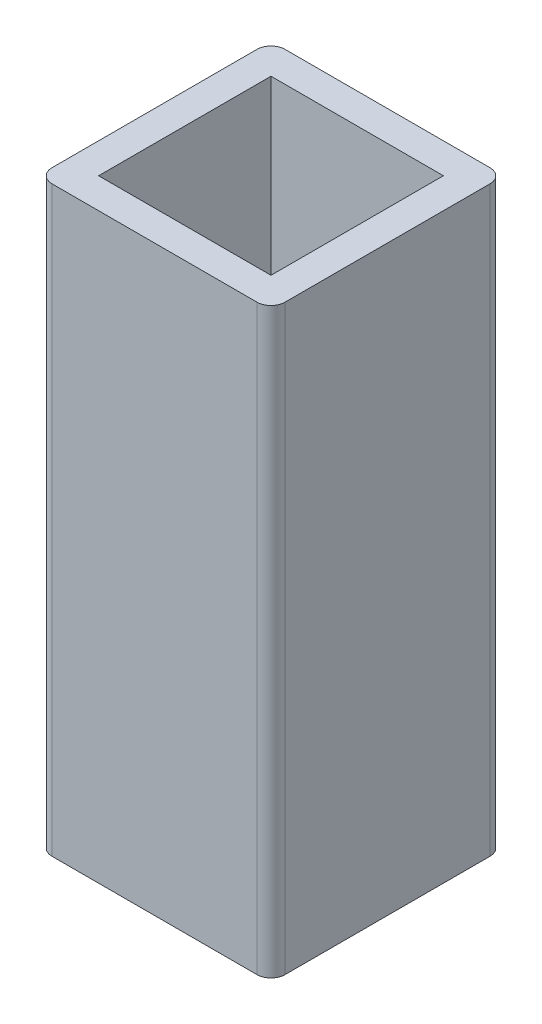
SolidWorks part; units mm, degrees
material "Plain Carbon Steel"
ref_plane "Front Plane" through (0, 0, 0) normal (0, 0, 1) x (1, 0, 0)
ref_plane "Top Plane" through (0, 0, 0) normal (0, 1, 0) x (1, 0, 0)
ref_plane "Right Plane" through (0, 0, 0) normal (1, 0, 0) x (0, 0, -1)
sketch "Sketch1" plane through (0, 0, 0) normal (0, 1, 0) x (1, 0, 0)
  line L1 (-5.588, -6.35) -> (5.588, -6.35)
  line L2 (-6.35, -5.588) -> (-6.35, 5.588)
  line L3 (-5.588, 6.35) -> (5.588, 6.35)
  line L4 (6.35, -5.588) -> (6.35, 5.588)
  line L5 (0, 6.35) -> (0, -6.35) construction
  line L6 (-6.35, 0) -> (6.35, 0) construction
  line L10 (-4.699, -4.699) -> (-4.699, 4.699)
  line L11 (-4.699, 4.699) -> (4.699, 4.699)
  line L12 (4.699, -4.699) -> (4.699, 4.699)
  line L13 (-4.699, -4.699) -> (4.699, -4.699)
  arc A0 (-5.588, -6.35) -> (-6.35, -5.588) centre (-5.588, -5.588) cw
  arc A1 (5.588, -6.35) -> (6.35, -5.588) centre (5.588, -5.588) ccw
  arc A2 (5.588, 6.35) -> (6.35, 5.588) centre (5.588, 5.588) cw
  arc A3 (-6.35, 5.588) -> (-5.588, 6.35) centre (-5.588, 5.588) cw
  arc A8 (-4.699, 4.699) -> (-4.699, 4.699) centre (-4.699, 4.699) cw
  arc A9 (4.699, 4.699) -> (4.699, 4.699) centre (4.699, 4.699) cw
  arc A10 (4.699, -4.699) -> (4.699, -4.699) centre (4.699, -4.699) ccw
  arc A11 (-4.699, -4.699) -> (-4.699, -4.699) centre (-4.699, -4.699) cw
  point P0 (0, 0)
  point P11 (6.35, 6.35)
  point P14 (-6.35, 6.35)
  dimension "D2" = 0.762
  dimension "D1" = 12.7
  dimension "D3" = 1.651
extrude "Boss-Extrude1" add sketch "Sketch1" along normal blind 31.75
